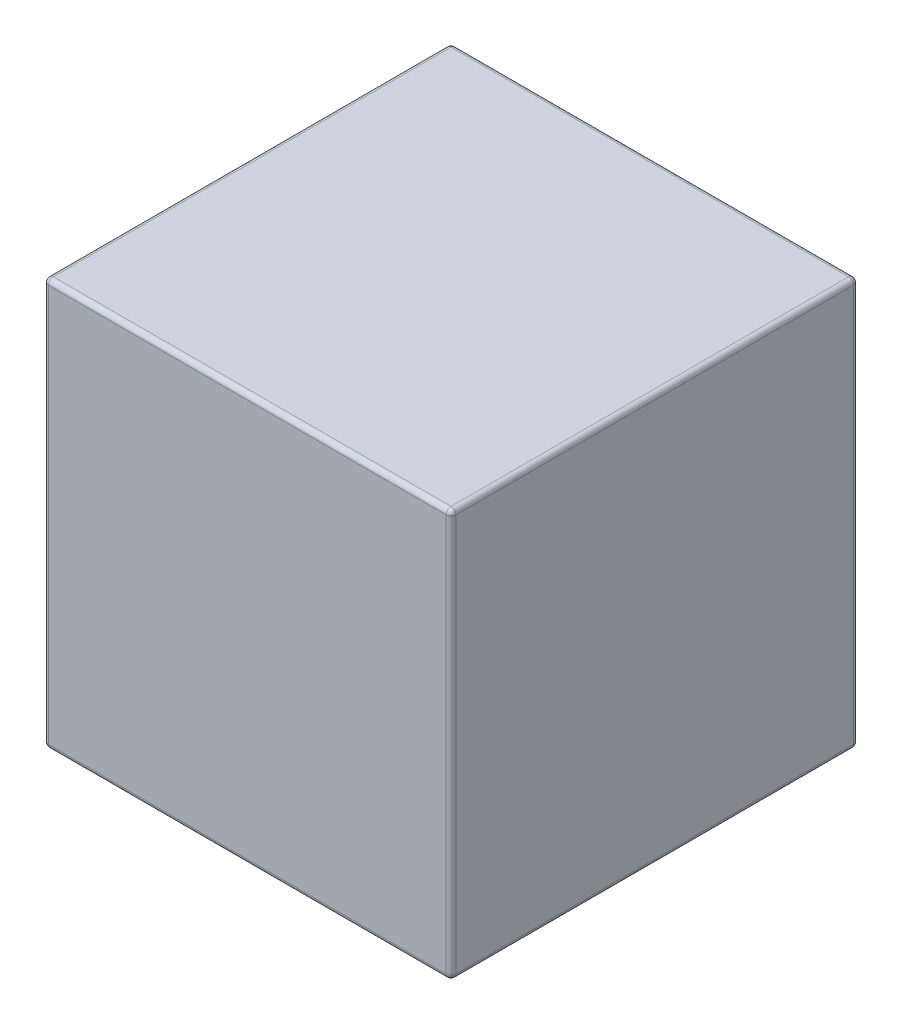
SolidWorks part; units mm, degrees
ref_plane "Plan de face" through (0, 0, 0) normal (0, 0, 1) x (1, 0, 0)
ref_plane "Plan de dessus" through (0, 0, 0) normal (0, 1, 0) x (1, 0, 0)
ref_plane "Plan de droite" through (0, 0, 0) normal (1, 0, 0) x (0, 0, -1)
sketch "Esquisse1" plane through (0, 0, 0) normal (0, 0, 1) x (1, 0, 0)
  line L1 (0, 0) -> (42, 0)
  line L2 (0, 0) -> (0, -42)
  line L3 (0, -42) -> (42, -42)
  line L4 (42, 0) -> (42, -42)
  dimension "D1" = 42
  dimension "D2" = 42
extrude "Boss.-Extru.1" add sketch "Esquisse1" along normal blind 42
sketch "Esquisse2" plane through (0, -42, 0) normal (0, -1, 0) x (1, 0, 0)
  line L0 (42, 42) -> (42, 0) construction
  line L1 (27.75, 38.25) -> (38.25, 38.25)
  line L2 (27.75, 38.25) -> (27.75, 27.75)
  line L3 (27.75, 27.75) -> (38.25, 27.75)
  line L4 (38.25, 38.25) -> (38.25, 27.75)
  line L5 (0, 42) -> (42, 42) construction
  line L13 (27.75, 14.25) -> (38.25, 14.25)
  line L14 (27.75, 14.25) -> (27.75, 3.75)
  line L15 (27.75, 3.75) -> (38.25, 3.75)
  line L16 (38.25, 14.25) -> (38.25, 3.75)
  point P4 (38.25, 9)
  point P7 (42, 21)
  point P8 (33, 38.25)
  point P11 (21, 42)
  point P16 (33, 27.75)
  point P17 (33, 14.25)
  point P18 (27.75, 33)
  dimension "D1" = 10.5
  dimension "D2" = 10.5
  dimension "D3" = 10.5
  dimension "D4" = 10.5
  dimension "D5" = 12
  dimension "D6" = 12
  dimension "D7" = 12
  dimension "D8" = 0
extrude "Enlèv. mat.-Extru.1" cut sketch "Esquisse2" against normal blind 4.5
ref_plane "Plan1" through (0, 0, 21) normal (0, 0, 1) x (1, 0, 0)
ref_plane "Plan2" through (21, 0, 0) normal (1, 0, 0) x (0, 0, -1)
ref_plane "Plan3" through (21, 0, 21) normal (0.7071, 0, 0.7071) x (0.7071, 0, -0.7071)
fillet "Congé1" radius 0.5 12 edges at (0, -42, 21) (21, -42, 42) (0, -21, 42) (42, -42, 21) (42, -21, 42) (21, -42, 0) (42, -21, 0) (0, -21, 0) (42, 0, 21) (21, 0, 42) (0, 0, 21) (21, 0, 0)
mirror "Symétrie1" about plane through (21, 0, 0) normal (1, 0, 0) of "Enlèv. mat.-Extru.1"
